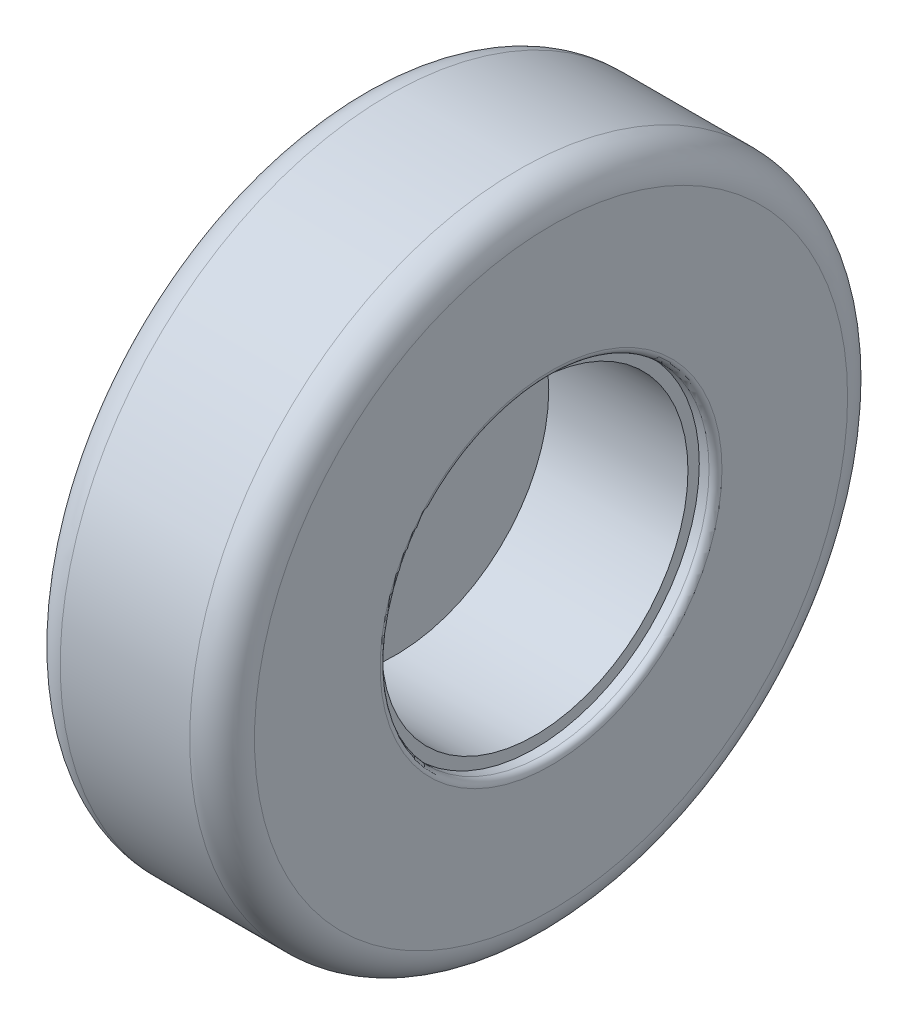
SolidWorks part; units mm, degrees
other "LHS Wheel" parameters "D1"=13.6453, "D2"=113.5139, "D3"=155.7266, "D4"=155.7266, "D19"=5
material "Rubber"
ref_plane "Front Plane" through (0, 0, 0) normal (0, 0, 1) x (1, 0, 0)
ref_plane "Top Plane" through (0, 0, 0) normal (0, 1, 0) x (1, 0, 0)
ref_plane "Right Plane" through (0, 0, 0) normal (1, 0, 0) x (0, 0, -1)
sketch "Sketch1" plane through (0, 0, 0) normal (1, 0, 0) x (0, 0, -1)
  circle A1 centre (0, 0) radius 7.625
  circle A2 centre (0, 0) radius 50.8
  dimension "D1" = 15.25
  dimension "D3" = 101.6
extrude "Hub Face" add sketch "Sketch1" along normal blind 7 from offset 5
sketch "Sketch2" plane through (0, 0, 0) normal (1, 0, 0) x (0, 0, -1)
  circle A0 centre (0, 0) radius 50.8
  circle A1 centre (0, 0) radius 47.3
  dimension "D1" = 101.6
  dimension "D2" = 94.6
extrude "Hub" add sketch "Sketch2" along normal blind 50 from offset 5
sketch "Sketch3" plane through (0, 0, 0) normal (1, 0, 0) x (0, 0, -1)
  circle A0 centre (0, 0) radius 101.6
  circle A1 centre (0, 0) radius 50.8
  dimension "D1" = 203.2
  dimension "D2" = 101.6
extrude "Rubber" add sketch "Sketch3" along normal blind 60
fillet "Fillet1" radius 10 2 edges at (0, 0, -101.6) (60, 0, -101.6)
fillet "Fillet2" radius 2 2 edges at (60, 0, -50.8) (0, 0, -50.8)
mirror "Mirror1" [suppressed] about plane through (0, 0, 0) normal (1, 0, 0)
equation "\"tireWidth\"= 60mm"
equation "\"tireDiameter\" = 8in"
equation "\"shaftDiameter\"= 15mm"
equation "\"hubDiameter\"= 4in"
equation "\"D1@Sketch1\"=\"shaftDiameter\" + 0.25mm"
equation "\"hubMaterialThickness\"= 7mm"
equation "\"D1@Hub Face\" = \"hubMaterialThickness\""
equation "\"D3@Sketch1\"=\"hubDiameter\""
equation "\"D1@Sketch2\"=\"hubDiameter\""
equation "\"D2@Sketch2\"=\"hubDiameter\"-\"hubMaterialThickness\""
equation "\"D1@Hub\"=\"hubWidth\""
equation "\"D1@Sketch3\"=\"tireDiameter\""
equation "\"D2@Sketch3\"=\"hubDiameter\""
equation "\"D1@Rubber\" = \"tireWidth\""
equation "\"hubWidth\"= 50mm"
equation "\"D19@Hub\"=(\"tireWidth\"-\"hubWidth\")/2"
equation "\"D19@Hub Face\"=(\"tireWidth\"-\"hubWidth\")/2"
